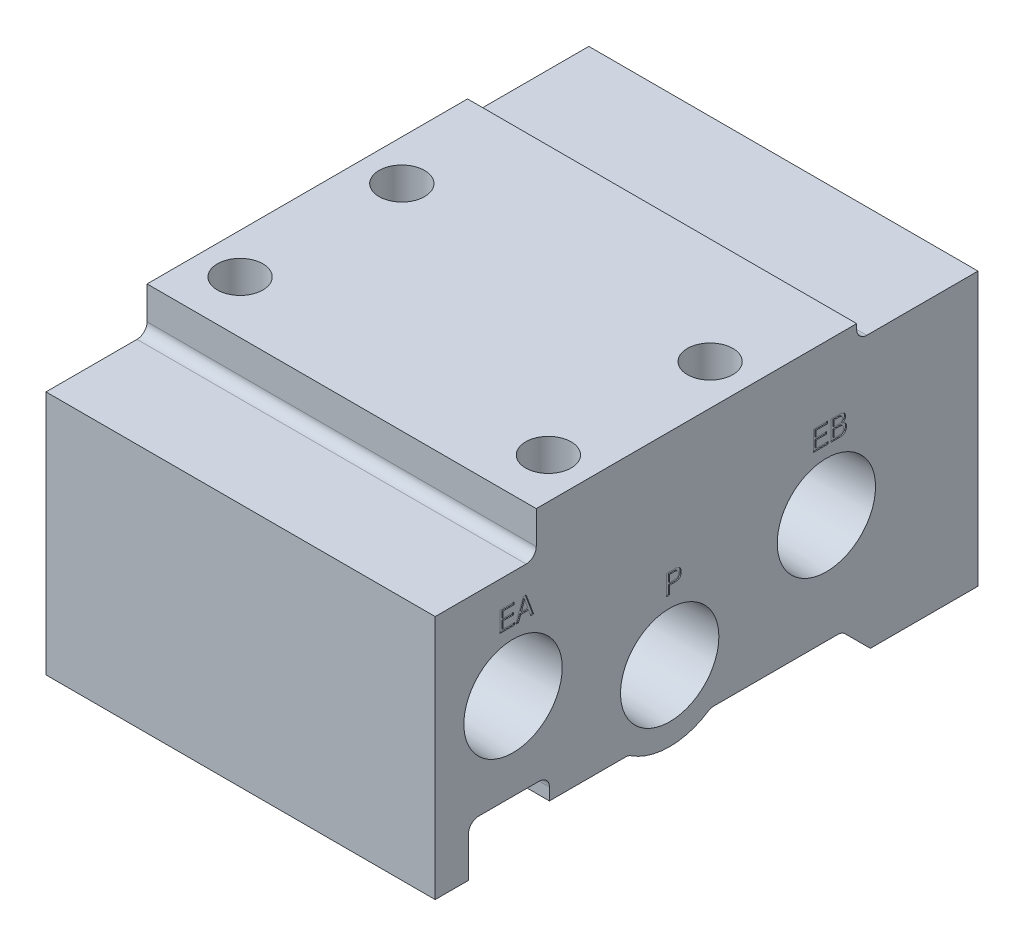
SolidWorks part; units mm, degrees
ref_plane "Front" through (0, 0, 0) normal (0, 0, 1) x (1, 0, 0)
ref_plane "Top" through (0, 0, 0) normal (0, 1, 0) x (1, 0, 0)
ref_plane "Right" through (0, 0, 0) normal (1, 0, 0) x (0, 0, -1)
sketch "Alum Ext Sketch" plane through (0, 0, 0) normal (1, 0, 0) x (0, 0, -1)
  line L1 (-26.85, 0) -> (26.85, 0)
  line L2 (-26.85, 0) -> (-26.85, -28.5)
  line L4 (26.85, 0) -> (26.85, -28.5)
  line L7 (0, 5.7104) -> (0, -31.2342) construction
  line L8 (-26.85, -28.5) -> (26.85, -28.5)
  dimension "Depth" = 53.7
  dimension "Height" = 28.5
extrude "Alum Ext" add sketch "Alum Ext Sketch" against normal up to surface (38.5 mm away)
sketch "Bottom_Profile 20 Sketch" [suppressed] plane through (0, 0, 0) normal (1, 0, 0) x (0, 0, -1)
  line L0 (-1, 0) -> (-1, -38.4475) construction
  line L1 (-21.54, -20) -> (-21.54, -13.45)
  line L2 (-24.5, -20) -> (24.5, -20) construction
  line L3 (-21.54, -13.45) -> (-21.1875, -13.45)
  line L4 (-13.8125, -13.45) -> (-4.6875, -13.45)
  line L5 (11.8125, -13.45) -> (2.6875, -13.45)
  line L6 (21.54, -13.45) -> (19.1875, -13.45)
  line L7 (21.54, -20) -> (21.54, -13.45)
  line L8 (24.5, -20) -> (24.5, 0) construction
  line L9 (-24.5, 0) -> (-24.5, -20) construction
  line L10 (24.5, 0) -> (-24.5, 0) construction
  line L11 (21.54, -16.725) -> (24.5, -16.725) construction
  line L12 (-21.54, -16.725) -> (-24.5, -16.725) construction
  line L13 (-24.5, -20) -> (-24.5, 0) construction
  line L14 (-21.54, -20) -> (21.54, -20)
  line L15 (-10.2716, -5) -> (-8.2284, -5)
  line L17 (-10.9481, -11.65) -> (-7.5519, -11.65)
  line L18 (-1, 9.9528) -> (-1, -11.3216) construction
  line L19 (8.9481, -11.65) -> (5.5519, -11.65)
  line L20 (8.2716, -5) -> (6.2284, -5)
  line L21 (24.5, 0) -> (-24.5, 0) construction
  arc A0 (-21.1875, -13.45) -> (-13.8125, -13.45) centre (-17.5, -7.5) ccw
  arc A1 (-4.6875, -13.45) -> (2.6875, -13.45) centre (-1, -7.5) ccw
  arc A2 (19.1875, -13.45) -> (11.8125, -13.45) centre (15.5, -7.5) cw
  arc A3 (-10.7535, -5.6333) -> (-11.3849, -10.9067) centre (-17.5, -7.5) cw
  arc A4 (-10.7535, -5.6333) -> (-10.2716, -5) centre (-10.2716, -5.5) cw
  arc A5 (-10.9481, -11.65) -> (-11.3849, -10.9067) centre (-10.9481, -11.15) cw
  arc A6 (-7.5519, -11.65) -> (-7.1151, -10.9067) centre (-7.5519, -11.15) ccw
  arc A7 (-7.7465, -5.6333) -> (-8.2284, -5) centre (-8.2284, -5.5) ccw
  arc A8 (-7.7465, -5.6333) -> (-7.1151, -10.9067) centre (-1, -7.5) ccw
  arc A9 (5.7465, -5.6333) -> (5.1151, -10.9067) centre (-1, -7.5) cw
  arc A10 (5.7465, -5.6333) -> (6.2284, -5) centre (6.2284, -5.5) cw
  arc A11 (5.5519, -11.65) -> (5.1151, -10.9067) centre (5.5519, -11.15) cw
  arc A12 (8.9481, -11.65) -> (9.3849, -10.9067) centre (8.9481, -11.15) ccw
  arc A13 (8.7535, -5.6333) -> (8.2716, -5) centre (8.2716, -5.5) ccw
  arc A14 (8.7535, -5.6333) -> (9.3849, -10.9067) centre (15.5, -7.5) ccw
  dimension "D1" = 23.5
  dimension "Wall_Radius" = 7
  dimension "D2" = 0.5
  dimension "D4" = 5
  dimension "D3" = 1.8
  dimension "Thickness" = 2.96
  dimension "Port_Loc_Z" = 16.5
  dimension "Port_Loc_Y" = 12.5
  dimension "Body_Thickness" = 13.45
extrude "Bottom_Profile 20" [suppressed] cut sketch "Bottom_Profile 20 Sketch" against normal through all
fillet "Ext_Fillets" [suppressed] radius 0.25
sketch "MGT_Holes Sketch" plane through (0, 0, 0) normal (0, 1, 0) x (1, 0, 0)
  line L1 (-19.25, 26.85) -> (-19.25, -50.1534) construction
  line L2 (-38.5, 26.85) -> (0, 26.85) construction
  line L3 (0, 0) -> (0, 12.4211) construction
  line L4 (-38.5, -26.85) -> (0, -26.85) construction
  line L6 (-38.5, -26.85) -> (-38.5, 26.85) construction
  circle A0 centre (-34.5, 4.35) radius 2.25
  circle A1 centre (-34.5, -11.65) radius 2.25
  circle A4 centre (-4, 4.35) radius 2.25
  circle A5 centre (-4, -11.65) radius 2.25
  dimension "Dia" = 4.5
  dimension "Loc_X" = 4
  dimension "Loc_Z" = 15.2
  dimension "C_2_C" = 16
extrude "MGT_Holes" cut sketch "MGT_Holes Sketch" against normal through all
sketch "Top_Profile_41 Sketch" plane through (0, 0, 0) normal (1, 0, 0) x (0, 0, -1)
  line L0 (-26.85, -4.25) -> (-16.85, -4.25)
  line L1 (-16.85, -4.25) -> (-16.85, 0)
  line L2 (26.85, 0) -> (-26.85, 0) construction
  line L3 (14.85, 0) -> (14.85, -1.5)
  line L4 (14.85, -1.5) -> (26.85, -1.5)
  line L5 (26.85, -28.5) -> (26.85, 0) construction
  line L6 (-26.85, -28.5) -> (26.85, -28.5) construction
  line L7 (-26.85, 0) -> (-26.85, -28.5) construction
  line L8 (26.85, -1.5) -> (26.85, 0)
  line L9 (-26.85, 0) -> (-26.85, -4.25)
  line L10 (26.85, 0) -> (14.85, 0)
  line L11 (-16.85, 0) -> (-26.85, 0)
  dimension "Back" = 12
  dimension "Back Height" = 27
  dimension "Front" = 10
  dimension "Front_Height" = 24.25
extrude "Top_Profile_41" cut sketch "Top_Profile_41 Sketch" against normal through all
sketch "Bottom_Profile_41 Sketch" plane through (0, 0, 0) normal (1, 0, 0) x (0, 0, -1)
  line L0 (16.2, -28.5) -> (13.4, -25.7)
  line L1 (-26.85, -28.5) -> (26.85, -28.5) construction
  line L2 (13.4, -25.7) -> (0.4132, -25.7)
  line L3 (-15.55, -25.7) -> (-15.55, -23.5)
  line L4 (-15.55, -23.5) -> (-23.55, -23.5)
  line L5 (-23.55, -23.5) -> (-23.55, -28.5)
  line L6 (26.85, -28.5) -> (-26.85, -28.5) construction
  line L7 (26.85, -28.5) -> (26.85, -1.5) construction
  line L8 (-26.85, -4.25) -> (-26.85, -28.5) construction
  line L9 (-26.85, -28.5) -> (-26.85, -4.25) construction
  line L10 (-7.7132, -25.7) -> (-15.55, -25.7)
  line L11 (-23.55, -28.5) -> (16.2, -28.5)
  arc A0 (-7.7132, -25.7) -> (0.4132, -25.7) centre (-3.65, -20) ccw
  dimension "D1" = 8.5
  dimension "D2" = 23.2
  dimension "Radius" = 7
  dimension "Back_Width" = 13.45
  dimension "Back_Depth" = 2.8
  dimension "Front_Width" = 3.3
  dimension "Front_Depth" = 5
  dimension "Groove" = 8
  dimension "Angle" = 45
extrude "Bottom_Profile_41" cut sketch "Bottom_Profile_41 Sketch" against normal through all
fillet "Rounds_41" radius 1 7 edges at (-19.25, -4.25, 16.85) (-19.25, -1.5, -14.85) (-19.25, -25.7, -0.4132) (-19.25, -23.5, 23.55) (-19.25, -23.5, 15.55) (-19.25, -25.7, 7.7132) (-19.25, -25.7, -13.4)
sketch "Profile_42 Sketch" [suppressed] plane through (0, 0, 0) normal (1, 0, 0) x (0, 0, -1)
  line L0 (-13.9, -32) -> (-12.9, -31)
  line L1 (-27.85, -32) -> (27.85, -32) construction
  line L2 (-12.9, -31) -> (12.9, -31)
  line L3 (12.9, -31) -> (13.9, -32)
  line L4 (13.9, -32) -> (-13.9, -32)
  line L5 (0, 0) -> (0, -41.5568) construction
  dimension "Width" = 25.8
  dimension "Angle" = 90
  dimension "Depth" = 1
extrude "Profile_42" [suppressed] cut sketch "Profile_42 Sketch" against normal through all
fillet "Fillets_42" [suppressed] radius 0.5
sketch "20 Port Designations Sketch" [suppressed] plane through (2.9671, 0, 3.015) normal (0, 1, 0) x (0, 0, 1)
  line L0 (21.485, -51.4671) -> (-27.515, -51.4671) construction
  line L2 (-27.515, -51.4671) -> (-27.515, -2.9671) construction
  line L3 (21.485, -51.4671) -> (21.485, -2.9671) construction
  text T0 "EA"
  text T1 "P" font "Swis721 BT" height 3.5
  text T2 "EB" font "Swis721 BT" height 3.5
  dimension "D1" = 3
  dimension "D2" = 4
  dimension "D3" = 23
  dimension "D4" = 11
extrude "20 Port Designations" [suppressed] cut sketch "20 Port Designations Sketch" against normal blind 0.1
sketch "20 Port Designations2 Sketch" [suppressed] plane through (-31.3648, 0, 0.1552) normal (0, 1, 0) x (0, 0, -1)
  line L0 (24.6552, -31.3648) -> (-24.3448, -31.3648) construction
  line L1 (24.6552, 17.1352) -> (24.6552, -31.3648) construction
  line L2 (-24.3448, 17.1352) -> (-24.3448, -31.3648) construction
  text T0 "EB"
  text T1 "P"
  text T2 "EA"
  dimension "D1" = 3
  dimension "D2" = 26.5
  dimension "D3" = 4
  dimension "D4" = 11
extrude "20 Port Designations2" [suppressed] cut sketch "20 Port Designations2 Sketch" against normal blind 0.1
hole_wizard "Ports" positions "Ports Loc Sketch" profile "Ports Profile Sketch" size "1/8" standard "ISO"
sketch "Ports Loc Sketch" plane through (0, 0, 0) normal (1, 0, 0) x (0, 0, -1)
  line L1 (-3.65, -20) -> (-3.65, -0.9405) construction
  line L5 (-26.85, -28.5) -> (-23.55, -28.5) construction
  line L7 (-26.85, -4.25) -> (-26.85, -28.5) construction
  point P0 (-3.65, -20)
  point P1 (11.85, -14.9)
  point P3 (-19.15, -14.9)
  dimension "Loc_Z" = 23.2
  dimension "C_2_C-Z" = 15.5
  dimension "C_2_C-Y" = 8.5
  dimension "Loc_Y" = 13.6
sketch "Ports Profile Sketch" plane through (0, -20, 3.65) normal (0, 1, 0) x (0, 0, -1)
  line L0 (0, 0) -> (0, 22.45)
  line L1 (3.95, 18.5) -> (0, 22.45)
  line L2 (-3.95, 18.5) -> (0, 22.45) construction
  line L3 (3.95, 18.5) -> (3.95, 7.4)
  line L4 (3.95, 7.4) -> (4.633, 7.4)
  line L5 (4.633, 7.4) -> (4.864, 0)
  line L6 (-4.633, 7.4) -> (-4.864, 0) construction
  line L7 (4.864, 0) -> (0, 0)
  line L8 (0, -6.35) -> (0, 107.95) construction
  line L11 (-3.95, 7.4) -> (-4.633, 7.4) construction
  dimension "Tap Drill Dia." = 7.9
  dimension "Tap Drill Depth" = 18.5
  dimension "Thread Dia." = 9.728
  dimension "Thread Angle" = 3.576
  dimension "Thread Depth" = 7.4
  dimension "Drill Angle" = 90
hole_wizard "Ports Mirror" positions "Ports Mirror Loc Sketch" profile "Ports Mirror Profile Sketch" size "1/8" standard "ISO"
sketch "Ports Mirror Loc Sketch" plane through (-38.5, 0, 0) normal (-1, 0, 0) x (0, 0, 1)
  point P0 (-11.85, -14.9)
  point P1 (3.65, -20)
  point P4 (19.15, -14.9)
sketch "Ports Mirror Profile Sketch" plane through (-38.5, -14.9, -11.85) normal (0, 1, 0) x (0, 0, 1)
  line L0 (0, 0) -> (0, 15.885)
  line L1 (3.95, 11.935) -> (0, 15.885)
  line L2 (-3.95, 11.935) -> (0, 15.885) construction
  line L3 (3.95, 11.935) -> (3.95, 7.4)
  line L4 (3.95, 7.4) -> (4.633, 7.4)
  line L5 (4.633, 7.4) -> (4.864, 0)
  line L6 (-4.633, 7.4) -> (-4.864, 0) construction
  line L7 (4.864, 0) -> (0, 0)
  line L8 (0, -6.35) -> (0, 107.95) construction
  line L11 (-3.95, 7.4) -> (-4.633, 7.4) construction
  dimension "Tap Drill Dia." = 7.9
  dimension "Tap Drill Depth" = 11.935
  dimension "Thread Dia." = 9.728
  dimension "Thread Angle" = 3.576
  dimension "Thread Depth" = 7.4
  dimension "Drill Angle" = 90
hole_wizard "Pilot Ports" [suppressed] positions "Pilot Ports Loc Sketch" profile "Pilot Ports Profile Sketch" tap size "M5x0.8" standard "JIS"
sketch "Pilot Ports Loc Sketch" [suppressed] plane through (0, 0, 0) normal (1, 0, 0) x (0, 0, -1)
  line L1 (14.1071, -32) -> (27.85, -32) construction
  circle A0 centre (-4.65, -24) radius 4.864 construction
  point P0 (14.75, -4)
  point P1 (-19.35, -4)
  dimension "D2" = 19.4
  dimension "D3" = 14.7
  dimension "D1" = 28
sketch "Pilot Ports Profile Sketch" [suppressed] plane through (0, -4, -14.75) normal (0, 1, 0) x (0, 0, -1)
  line L0 (0, 0) -> (0, 13.6618)
  line L1 (0, 13.6618) -> (2.1, 12.4)
  line L2 (2.1, 12.4) -> (2.1, 10)
  line L3 (2.1, 10) -> (2.5, 10)
  line L4 (2.5, 10) -> (2.5, 0)
  line L5 (2.5, 0) -> (0, 0)
  line L10 (0, 13.6618) -> (-2.1, 12.4) construction
  line L11 (0, -6.35) -> (0, 107.95) construction
  dimension "Tap Drill Dia." = 4.2
  dimension "Tap Drill Depth" = 12.4
  dimension "Thread Major Dia." = 5
  dimension "Thread Depth" = 10
  dimension "Drill Angle" = 118
hole_wizard "Pilot Ports Mirror" [suppressed] positions "Pilot Ports Mirror Loc Sketch" profile "Pilot Ports Mirror Profile Sketch" tap size "M5" standard "ISO"
sketch "Pilot Ports Mirror Loc Sketch" [suppressed] plane through (-227.5, 0, 0) normal (-1, 0, 0) x (0, 0, 1)
  point P0 (19.35, -4)
  point P1 (-14.75, -4)
sketch "Pilot Ports Mirror Profile Sketch" [suppressed] plane through (-227.5, -4, 19.35) normal (0, 1, 0) x (0, 0, 1)
  line L0 (0, 0) -> (0, 13.6618)
  line L1 (0, 13.6618) -> (2.1, 12.4)
  line L2 (2.1, 12.4) -> (2.1, 10)
  line L3 (2.1, 10) -> (2.5, 10)
  line L4 (2.5, 10) -> (2.5, 0)
  line L5 (2.5, 0) -> (0, 0)
  line L10 (0, 13.6618) -> (-2.1, 12.4) construction
  line L11 (0, -6.35) -> (0, 107.95) construction
  dimension "Tap Drill Dia." = 4.2
  dimension "Tap Drill Depth" = 12.4
  dimension "Thread Major Dia." = 5
  dimension "Thread Depth" = 10
  dimension "Drill Angle" = 118
sketch "41,42 Port Labels1 Sketch" plane through (-38.5, 0, 0) normal (-1, 0, 0) x (0, 0, 1)
  text T0 "EB" font "Swis721 BT" height 2
  text T1 "P" font "Swis721 BT" height 2
  text T2 "EA" font "Swis721 BT" height 2
  dimension "D1" = 1.5
  dimension "D2" = 1.5
  dimension "D3" = 6
  dimension "D4" = 6
  dimension "D5" = 6
  dimension "D6" = 0.5
extrude "41,42 Port Labels1" cut sketch "41,42 Port Labels1 Sketch" against normal blind 0.1
sketch "41,42 Port Labels2 Sketch" plane through (0, 0, 0) normal (1, 0, 0) x (0, 0, -1)
  text T0 "EA" font "Swis721 BT" height 2
  text T1 "P" font "Swis721 BT" height 2
  text T2 "EB" font "Swis721 BT" height 2
  dimension "D1" = 6
  dimension "D2" = 6
  dimension "D3" = 0.5
  dimension "D4" = 6
  dimension "D5" = 1.5
  dimension "D6" = 1.5
extrude "41,42 Port Labels2" cut sketch "41,42 Port Labels2 Sketch" against normal blind 0.1
sketch "42 Pilot Labels1 Sketch" [suppressed] plane through (-227.5, 0, 0) normal (-1, 0, 0) x (0, 0, 1)
  text T0 "PE" font "Swis721 BT" height 2
  text T1 "X" font "Swis721 BT" height 2
extrude "42 Pilot Labels1" [suppressed] cut sketch "42 Pilot Labels1 Sketch" against normal blind 0.1
sketch "42 Pilot Labels2 Sketch" [suppressed] plane through (0, 0, 0) normal (1, 0, 0) x (0, 0, -1)
  text T0 "X" font "Swis721 BT" height 2
  text T1 "PE" font "Swis721 BT" height 2
extrude "42 Pilot Labels2" [suppressed] cut sketch "42 Pilot Labels2 Sketch" against normal blind 0.1
sketch "41,42 A,B Labels Sketch" plane through (0, 0, -26.85) normal (0, 0, 1) x (1, 0, 0)
  line L0 (-38.5, -28.5) -> (0, -28.5) construction
  line L1 (-38.5, -1.5) -> (-38.5, -28.5) construction
  line L2 (0, -28.5) -> (0, -1.5) construction
  line L3 (-38.5, -28.5) -> (0, -28.5) construction
  text T0 "A"
  text T1 "B"
  text T2 "A"
  text T3 "B"
  point P12 (-38.5, -15)
  dimension "D1" = 5
  dimension "D2" = 11
  dimension "D3" = 1
  dimension "D4" = 18.5
  dimension "D5" = 8
  dimension "D6" = 4.5
extrude "41,42 A,B Labels" cut sketch "41,42 A,B Labels Sketch" along normal blind 0.1
